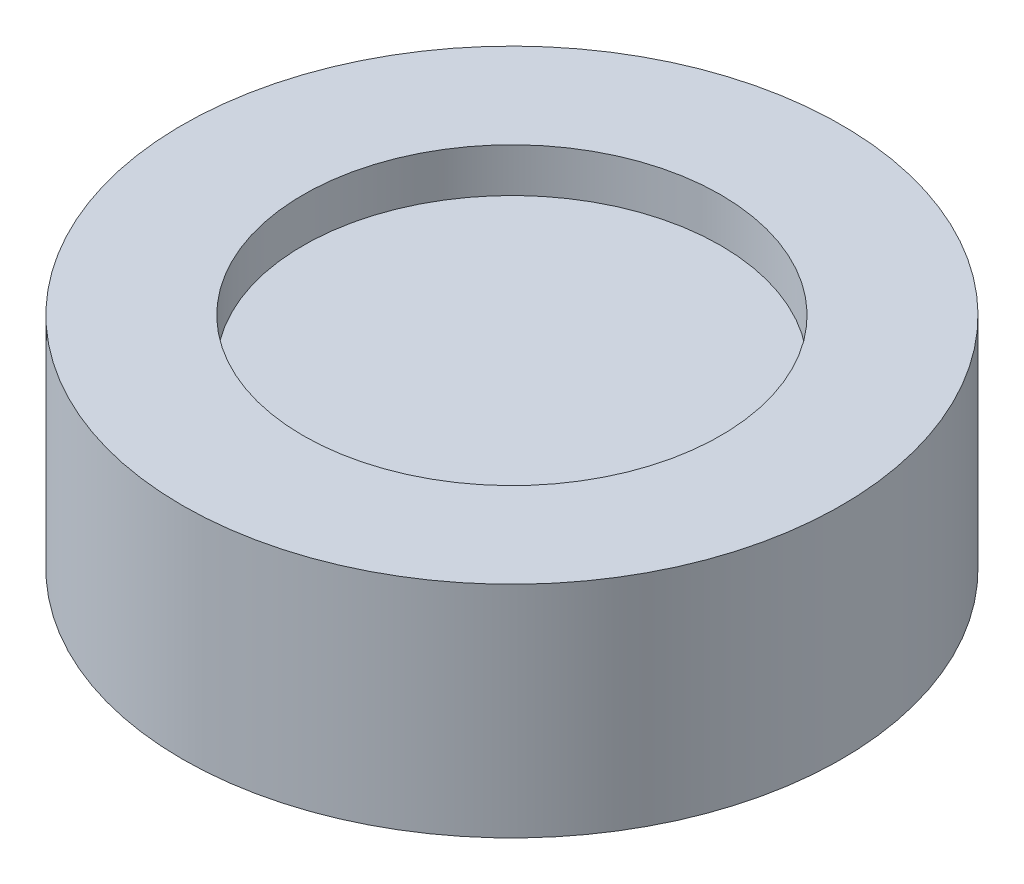
SolidWorks part; units mm, degrees
ref_plane "Front Plane" through (0, 0, 0) normal (0, 0, 1) x (1, 0, 0)
ref_plane "Top Plane" through (0, 0, 0) normal (0, 1, 0) x (1, 0, 0)
ref_plane "Right Plane" through (0, 0, 0) normal (1, 0, 0) x (0, 0, -1)
sketch "Sketch1" plane through (0, 0, 0) normal (0, 1, 0) x (1, 0, 0)
  circle A0 centre (0, 0) radius 38.1
extrude "Boss-Extrude1" add sketch "Sketch1" along normal blind 12.7
sketch "Sketch2" plane through (0, 12.7, 0) normal (0, 1, 0) x (1, 0, 0)
  circle A0 centre (0, 0) radius 24.13
extrude "Cut-Extrude1" cut sketch "Sketch2" against normal blind 5.08
mirror "Mirror1" about plane through (0, 0, 0) normal (0, 1, 0) of "Cut-Extrude1", "Boss-Extrude1"
